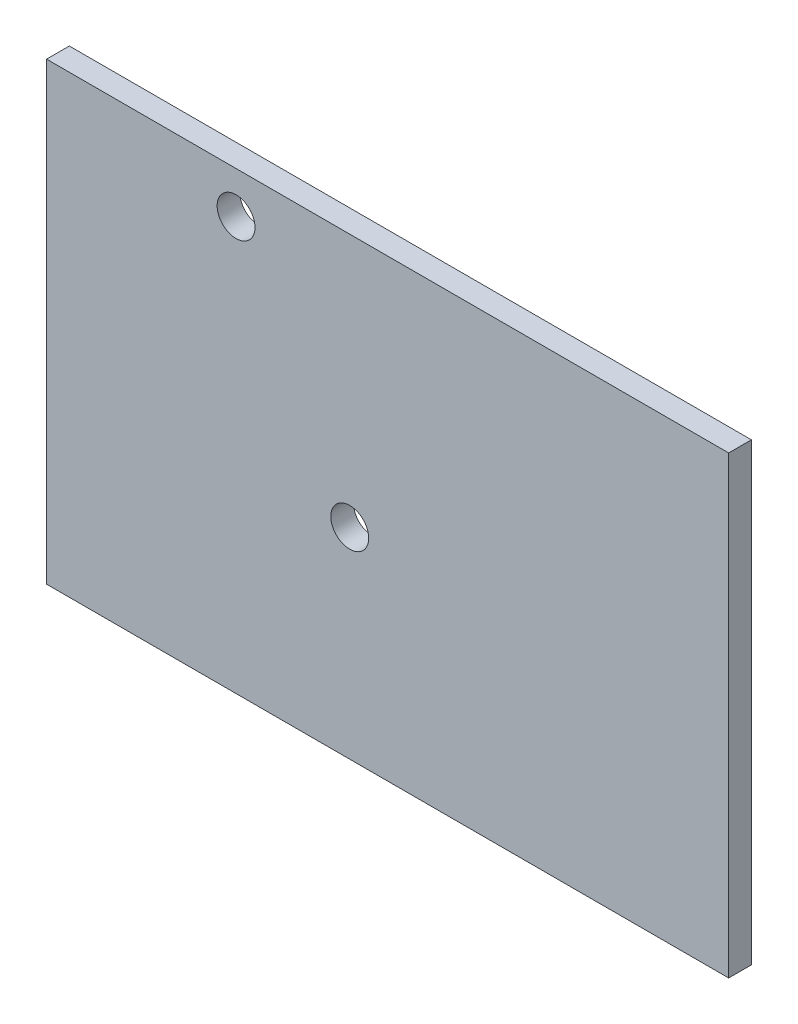
SolidWorks part; units mm, degrees
ref_plane "정면" through (0, 0, 0) normal (0, 0, 1) x (1, 0, 0)
ref_plane "윗면" through (0, 0, 0) normal (0, 1, 0) x (1, 0, 0)
ref_plane "우측면" through (0, 0, 0) normal (1, 0, 0) x (0, 0, -1)
sketch "스케치1" plane through (0, 0, 0) normal (0, 0, 1) x (1, 0, 0)
  line L1 (-45, 30) -> (45, 30)
  line L2 (-45, 30) -> (-45, -30)
  line L3 (-45, -30) -> (45, -30)
  line L4 (45, 30) -> (45, -30)
  line L5 (-45, 30) -> (45, -30) construction
  line L6 (-45, -30) -> (45, 30) construction
  circle A0 centre (-20, 24.5) radius 2.5
  circle A1 centre (-5, -3.5) radius 2.5
  point P0 (0, 0)
  dimension "D4" = 5
  dimension "D6" = 5
  dimension "D1" = 90
  dimension "D2" = 60
  dimension "D3" = 5.5
  dimension "D5" = 25
  dimension "D7" = 15
  dimension "D8" = 28
extrude "보스-돌출1" add sketch "스케치1" along normal blind 3
